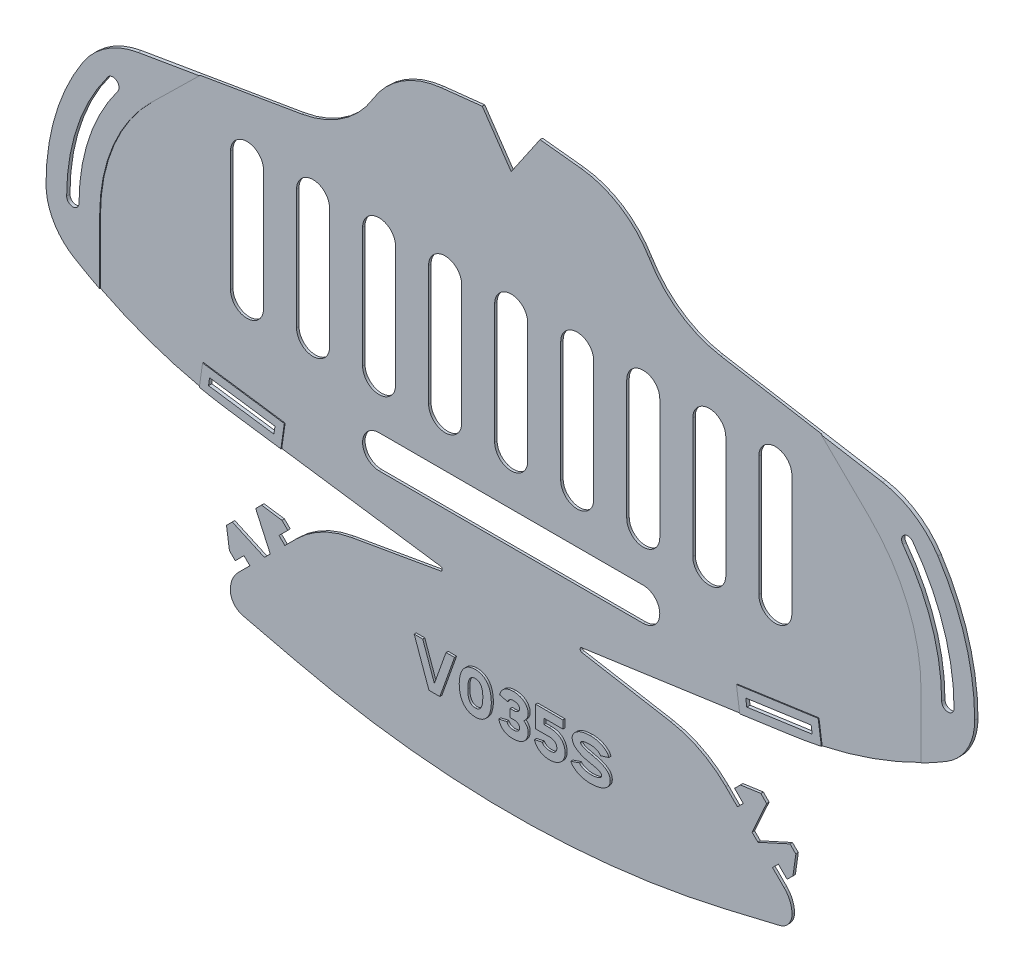
SolidWorks part; units mm, degrees
ref_plane "Front Plane" through (0, 0, 0) normal (0, 0, 1) x (1, 0, 0)
ref_plane "Top Plane" through (0, 0, 0) normal (0, 1, 0) x (1, 0, 0)
ref_plane "Right Plane" through (0, 0, 0) normal (1, 0, 0) x (0, 0, -1)
sketch "Sketch1" plane through (0, 0, 0) normal (0, 0, 1) x (1, 0, 0)
  line L0 (0, 0) -> (0, -145) construction
  line L1 (-14, -102) -> (14, -102) construction
  line L2 (-112.5, -69) -> (112.5, -69) construction
  line L3 (0, -10.2352) -> (-7, 0)
  line L4 (0, -10.2352) -> (7, 0)
  line L5 (7, 0) -> (16.9419, -1.0768)
  line L6 (-90.1804, -30.1909) -> (-50.7439, -23.5)
  line L7 (90.1804, -30.1909) -> (50.7439, -23.5)
  line L8 (-14, -102) -> (-68.2662, -94.2919)
  line L9 (-7, 0) -> (-16.9419, -1.0768)
  line L10 (14, -102) -> (68.2662, -94.2919)
  line L11 (-103.5977, -39) -> (-103.5977, -69) construction
  line L12 (-14, -102) -> (-38.6266, -106.305)
  line L13 (-52, -113.2546) -> (-54.8283, -116.0832)
  line L14 (52, -113.2546) -> (54.8283, -116.0832)
  line L15 (14, -102) -> (38.6266, -106.305)
  line L16 (-54.8283, -116.0832) -> (-56.2426, -114.669)
  line L17 (-56.2426, -114.669) -> (-54.1214, -112.5476)
  line L18 (-54.1214, -112.5476) -> (-55.5356, -111.1334)
  line L19 (-55.5356, -111.1334) -> (-60.4854, -110.4265)
  line L20 (-60.4854, -110.4265) -> (-68.9703, -118.9122)
  line L21 (-64.7275, -123.1546) -> (-63.3132, -124.5688)
  line L22 (-63.3132, -124.5688) -> (-66.1415, -127.3973)
  line L23 (-64.7275, -123.1546) -> (-66.8487, -125.2761)
  line L24 (-66.8487, -125.2761) -> (-68.263, -123.8619)
  line L25 (-68.9703, -118.9122) -> (-68.263, -123.8619)
  line L26 (68.9703, -118.9122) -> (68.263, -123.8619)
  line L27 (66.8487, -125.2761) -> (68.263, -123.8619)
  line L28 (64.7275, -123.1546) -> (66.8487, -125.2761)
  line L29 (63.3132, -124.5688) -> (66.1415, -127.3973)
  line L30 (64.7275, -123.1546) -> (63.3132, -124.5688)
  line L31 (60.4854, -110.4265) -> (68.9703, -118.9122)
  line L32 (55.5356, -111.1334) -> (60.4854, -110.4265)
  line L33 (54.1214, -112.5476) -> (55.5356, -111.1334)
  line L34 (56.2426, -114.669) -> (54.1214, -112.5476)
  line L35 (54.8283, -116.0832) -> (56.2426, -114.669)
  line L36 (-64.9691, -135.8852) -> (-52.4361, -138.8607)
  line L37 (64.9691, -135.8852) -> (52.4361, -138.8607)
  line L38 (-68.9703, -118.9122) -> (-64.7275, -123.1546) construction
  line L39 (-60.4854, -110.4265) -> (-56.2426, -114.669) construction
  arc A0 (-16.9419, -1.0768) -> (-33.4614, -11.6696) centre (-14.5729, -22.9489) ccw
  arc A1 (-33.4614, -11.6696) -> (-50.7439, -23.5) centre (-54.9257, 1.1478) cw
  arc A2 (-103.5977, -39) -> (-90.1804, -30.1909) centre (-86.8349, -49.9091) cw
  arc A3 (-112.5, -69) -> (-103.5977, -39) centre (-57.5, -69) cw
  arc A4 (112.5, -69) -> (103.5977, -39) centre (57.5, -69) ccw
  arc A5 (103.5977, -39) -> (90.1804, -30.1909) centre (86.8349, -49.9091) ccw
  arc A6 (16.9419, -1.0768) -> (33.4614, -11.6696) centre (14.5729, -22.9489) cw
  arc A7 (33.4614, -11.6696) -> (50.7439, -23.5) centre (54.9257, 1.1478) ccw
  arc A8 (-112.5, -69) -> (-105.7111, -81) centre (-98.5, -69) ccw
  arc A9 (-105.7111, -81) -> (-68.2662, -94.2919) centre (-54.2032, 4.7143) ccw
  arc A10 (112.5, -69) -> (105.7111, -81) centre (98.5, -69) cw
  arc A11 (105.7111, -81) -> (68.2662, -94.2919) centre (54.2032, 4.7143) cw
  arc A12 (-38.6266, -106.305) -> (-52, -113.2546) centre (-34.3216, -130.9315) ccw
  arc A13 (38.6266, -106.305) -> (52, -113.2546) centre (34.3216, -130.9315) cw
  arc A14 (-66.1415, -127.3973) -> (-68.0451, -131.9933) centre (-61.5451, -131.9933) ccw
  arc A15 (-68.0451, -131.9933) -> (-64.9691, -135.8852) centre (-64.0451, -131.9933) ccw
  arc A16 (68.0451, -131.9933) -> (64.9691, -135.8852) centre (64.0451, -131.9933) cw
  arc A17 (66.1415, -127.3973) -> (68.0451, -131.9933) centre (61.5451, -131.9933) cw
  arc A19 (-52.4361, -138.8607) -> (0, -145) centre (0, 82) ccw
  arc A20 (52.4361, -138.8607) -> (0, -145) centre (0, 82) cw
  point P8 (0, -102)
  point P11 (0, -69)
  point P76 (0, 0)
  point P78 (0, 0)
  point P79 (0, 0)
  point P80 (0, 0)
  point P81 (0, 0)
  dimension "D5" = 55
  dimension "D11" = 20
  dimension "D13" = 25
  dimension "D16" = 14
  dimension "D15" = 22
  dimension "D18" = 100
  dimension "D22" = 25
  dimension "D31" = 6.5
  dimension "D32" = 4
  dimension "D34" = 227
  dimension "D1" = 145
  dimension "D2" = 28
  dimension "D3" = 43
  dimension "D4" = 76
  dimension "D6" = 225
  dimension "D7" = 14
  dimension "D8" = 12.4
  dimension "D9" = 10
  dimension "D10" = 30
  dimension "D12" = 40
  dimension "D14" = 45.5
  dimension "D17" = 12
  dimension "D19" = 18
  dimension "D20" = 25
  dimension "D21" = 4
  dimension "D23" = 38
  dimension "D24" = 2
  dimension "D25" = 3
  dimension "D26" = 2
  dimension "D27" = 18
  dimension "D29" = 8
  dimension "D30" = 4
extrude "Main Shape" add sketch "Sketch1" along normal blind 0.6
sketch "Sketch2" plane through (0, 0, 0.6) normal (0, 0, 1) x (1, 0, 0)
  line L0 (0, -55) -> (0, 55) construction
  arc A0 (-96.3, -39.9) -> (-106, -69) centre (-57.5, -69) ccw construction
  arc A1 (-97.5, -39) -> (-107.5, -69) centre (-57.5, -69) ccw
  arc A2 (-95.1, -40.8) -> (-104.5, -69) centre (-57.5, -69) ccw
  arc A3 (-95.1, -40.8) -> (-97.5, -39) centre (-96.3, -39.9) ccw
  arc A4 (-107.5, -69) -> (-104.5, -69) centre (-106, -69) ccw
  arc A6 (-103.5977, -39) -> (-112.5, -69) centre (-57.5, -69) ccw construction
  arc A7 (96.3, -39.9) -> (106, -69) centre (57.5, -69) cw construction
  arc A8 (97.5, -39) -> (107.5, -69) centre (57.5, -69) cw
  arc A9 (95.1, -40.8) -> (104.5, -69) centre (57.5, -69) cw
  arc A10 (95.1, -40.8) -> (97.5, -39) centre (96.3, -39.9) cw
  arc A11 (107.5, -69) -> (104.5, -69) centre (106, -69) cw
  point P3 (-103.5111, -53.663)
  point P19 (103.5111, -53.663)
  dimension "D1" = 5
  dimension "D2" = 1.5
extrude "Elastic Attachment Points" cut sketch "Sketch2" against normal through all
sketch "Sketch7" plane through (0, 0, 0.6) normal (0, 0, 1) x (1, 0, 0)
  line L0 (-99.5, -69) -> (-99.5, -84.4384)
  line L1 (-86.8939, -39) -> (-75.3319, -27.6717)
  line L2 (-50.7439, -23.5) -> (-90.1804, -30.1909) construction
  line L3 (-75.3319, -27.6717) -> (-90.1804, -30.1909)
  line L4 (0, -55) -> (0, 55) construction
  line L5 (75.3319, -27.6717) -> (90.1804, -30.1909)
  line L6 (86.8939, -39) -> (75.3319, -27.6717)
  line L7 (99.5, -69) -> (99.5, -84.4384)
  arc A0 (-99.5, -69) -> (-86.8939, -39) centre (-57.5, -69) cw
  arc A1 (-95.1, -40.8) -> (-104.5, -69) centre (-57.5, -69) ccw construction
  arc A2 (-105.7111, -81) -> (-68.2662, -94.2919) centre (-54.2032, 4.7143) ccw construction
  arc A3 (-112.5, -69) -> (-105.7111, -81) centre (-98.5, -69) ccw construction
  arc A4 (-103.5977, -39) -> (-112.5, -69) centre (-57.5, -69) ccw construction
  arc A5 (-90.1804, -30.1909) -> (-103.5977, -39) centre (-86.8349, -49.9091) ccw construction
  arc A6 (-105.7111, -81) -> (-99.5, -84.4384) centre (-54.2032, 4.7143) ccw
  arc A7 (-112.5, -69) -> (-105.7111, -81) centre (-98.5, -69) ccw
  arc A8 (-103.5977, -39) -> (-112.5, -69) centre (-57.5, -69) ccw
  arc A9 (-90.1804, -30.1909) -> (-103.5977, -39) centre (-86.8349, -49.9091) ccw
  arc A10 (90.1804, -30.1909) -> (103.5977, -39) centre (86.8349, -49.9091) cw
  arc A11 (103.5977, -39) -> (112.5, -69) centre (57.5, -69) cw
  arc A12 (112.5, -69) -> (105.7111, -81) centre (98.5, -69) cw
  arc A13 (105.7111, -81) -> (99.5, -84.4384) centre (54.2032, 4.7143) cw
  arc A14 (99.5, -69) -> (86.8939, -39) centre (57.5, -69) ccw
  arc A15 (-107.5, -69) -> (-104.5, -69) centre (-106, -69) ccw construction
  arc A16 (-95.1, -40.8) -> (-97.5, -39) centre (-96.3, -39.9) ccw construction
  arc A17 (-97.5, -39) -> (-107.5, -69) centre (-57.5, -69) ccw construction
  arc A18 (-107.5, -69) -> (-104.5, -69) centre (-106, -69) ccw
  arc A19 (-95.1, -40.8) -> (-97.5, -39) centre (-96.3, -39.9) ccw
  arc A20 (-95.1, -40.8) -> (-104.5, -69) centre (-57.5, -69) ccw
  arc A21 (-97.5, -39) -> (-107.5, -69) centre (-57.5, -69) ccw
  arc A22 (104.5, -69) -> (107.5, -69) centre (106, -69) ccw construction
  arc A23 (97.5, -39) -> (95.1, -40.8) centre (96.3, -39.9) ccw construction
  arc A24 (104.5, -69) -> (95.1, -40.8) centre (57.5, -69) ccw construction
  arc A25 (107.5, -69) -> (97.5, -39) centre (57.5, -69) ccw construction
  arc A26 (104.5, -69) -> (107.5, -69) centre (106, -69) ccw
  arc A27 (97.5, -39) -> (95.1, -40.8) centre (96.3, -39.9) ccw
  arc A28 (104.5, -69) -> (95.1, -40.8) centre (57.5, -69) ccw
  arc A29 (107.5, -69) -> (97.5, -39) centre (57.5, -69) ccw
  dimension "D1" = 5
extrude "Reinforced Attachment Points" add sketch "Sketch7" along normal blind 0.2
sketch "Sketch6" plane through (0, 0, 0.6) normal (0, 0, 1) x (1, 0, 0)
  line L0 (-73.1225, -91.5821) -> (-57.2815, -93.8322)
  line L1 (-57.2815, -93.8322) -> (-57.0283, -92.05)
  line L2 (-57.0283, -92.05) -> (-72.8693, -89.8)
  line L3 (-72.8693, -89.8) -> (-73.1225, -91.5821)
  line L4 (-68.2662, -94.2919) -> (-14, -102) construction
  line L5 (-64.9488, -90.925) -> (-65.202, -92.7071) construction
  line L13 (0, -0.44) -> (0, 0.44) construction
  line L14 (64.9488, -90.925) -> (65.202, -92.7071) construction
  line L15 (73.1225, -91.5821) -> (72.8693, -89.8)
  line L16 (57.0283, -92.05) -> (57.2815, -93.8322)
  line L22 (57.0283, -92.05) -> (72.8693, -89.8)
  line L24 (73.1225, -91.5821) -> (57.2815, -93.8322)
  dimension "D1" = 2
  dimension "D2" = 16
  dimension "D3" = 52
  dimension "D4" = 1.8
extrude "Tab Slits" cut sketch "Sketch6" against normal through all
sketch "Sketch9" plane through (0, 0, 0.6) normal (0, 0, 1) x (1, 0, 0)
  line L4 (-57.2815, -93.8322) -> (-57.0283, -92.05) construction
  line L5 (-73.1225, -91.5821) -> (-57.2815, -93.8322) construction
  line L6 (-72.8693, -89.8) -> (-73.1225, -91.5821) construction
  line L7 (-57.0283, -92.05) -> (-72.8693, -89.8) construction
  line L12 (-57.2815, -93.8322) -> (-57.0283, -92.05)
  line L13 (-73.1225, -91.5821) -> (-57.2815, -93.8322)
  line L14 (-72.8693, -89.8) -> (-73.1225, -91.5821)
  line L15 (-57.0283, -92.05) -> (-72.8693, -89.8)
  line L16 (-55.5826, -96.0935) -> (-54.767, -90.3512)
  line L17 (-68.2662, -94.2919) -> (-14, -102) construction
  line L18 (-54.767, -90.3512) -> (-74.5682, -87.5386)
  line L19 (-74.5682, -87.5386) -> (-75.3475, -93.0248)
  line L20 (-68.2662, -94.2919) -> (-55.5826, -96.0935)
  line L21 (0, -0.44) -> (0, 0.44) construction
  line L22 (68.2662, -94.2919) -> (55.5826, -96.0935)
  line L23 (74.5682, -87.5386) -> (75.3475, -93.0248)
  line L24 (54.767, -90.3512) -> (74.5682, -87.5386)
  line L25 (55.5826, -96.0935) -> (54.767, -90.3512)
  line L26 (57.0283, -92.05) -> (72.8693, -89.8)
  line L27 (72.8693, -89.8) -> (73.1225, -91.5821)
  line L28 (73.1225, -91.5821) -> (57.2815, -93.8322)
  line L29 (57.2815, -93.8322) -> (57.0283, -92.05)
  arc A0 (-99.5, -84.4384) -> (-68.2662, -94.2919) centre (-54.2032, 4.7143) ccw construction
  arc A1 (-75.3475, -93.0248) -> (-68.2662, -94.2919) centre (-54.2032, 4.7143) ccw
  arc A2 (75.3475, -93.0248) -> (68.2662, -94.2919) centre (54.2032, 4.7143) cw
  dimension "D1" = 2
  dimension "D2" = 2
  dimension "D3" = 2
extrude "Reinforced Tab Slits" add sketch "Sketch9" along normal blind 0.2
sketch "Sketch11" plane through (0, 0, 0.6) normal (0, 0, 1) x (1, 0, 0)
  line L0 (-67.5562, -117.4979) -> (-59.7778, -121.0331)
  line L1 (-60.4854, -110.4265) -> (-68.9703, -118.9122) construction
  line L2 (-59.7778, -121.0331) -> (-58.3637, -119.6188)
  line L3 (-58.3637, -119.6188) -> (-61.8996, -111.8408)
  line L4 (-61.8996, -111.8408) -> (-67.5562, -117.4979)
  line L6 (-58.3637, -119.6188) -> (-54.8283, -116.0832) construction
  line L7 (-59.7778, -121.0331) -> (-63.3132, -124.5688) construction
  line L10 (0, -0.44) -> (0, 0.44) construction
  line L11 (59.7778, -121.0331) -> (63.3132, -124.5688) construction
  line L12 (58.3637, -119.6188) -> (54.8283, -116.0832) construction
  line L13 (61.8996, -111.8408) -> (67.5562, -117.4979)
  line L14 (58.3637, -119.6188) -> (61.8996, -111.8408)
  line L15 (59.7778, -121.0331) -> (58.3637, -119.6188)
  line L16 (67.5562, -117.4979) -> (59.7778, -121.0331)
  dimension "D1" = 2
  dimension "D2" = 2
  dimension "D3" = 5
extrude "Tab Flex Relief" cut sketch "Sketch11" against normal through all both and the other way through all
sketch "Sketch3" plane through (0, 0, 0.6) normal (0, 0, 1) x (1, 0, 0)
  line L3 (0, -10.2352) -> (0, -145) construction
  line L4 (-106, -69) -> (-96.3, -69) construction
  line L5 (-96.3, -69) -> (-96.3, -39.9) construction
  line L427 (0, -39.9) -> (0, -69) construction
  line L428 (4, -39.9) -> (4, -69)
  line L429 (-4, -39.9) -> (-4, -69)
  line L444 (-16, -39.9) -> (-16, -69) construction
  line L447 (-12, -39.9) -> (-12, -69)
  line L450 (-20, -39.9) -> (-20, -69)
  line L451 (-32, -39.9) -> (-32, -69) construction
  line L455 (-28, -39.9) -> (-28, -69)
  line L456 (-36, -39.9) -> (-36, -69)
  line L836 (-32, -85) -> (32, -85) construction
  line L837 (-32, -81) -> (32, -81)
  line L838 (-32, -89) -> (32, -89)
  line L839 (-64, -73) -> (64, -73) construction
  line L933 (-48, -39.9) -> (-48, -69) construction
  line L934 (-44, -39.9) -> (-44, -69)
  line L935 (-52, -39.9) -> (-52, -69)
  line L936 (-64, -39.9) -> (-64, -69) construction
  line L937 (-60, -39.9) -> (-60, -69)
  line L938 (-68, -39.9) -> (-68, -69)
  line L939 (16, -39.9) -> (16, -69) construction
  line L940 (12, -39.9) -> (12, -69)
  line L941 (20, -39.9) -> (20, -69)
  line L942 (32, -39.9) -> (32, -69) construction
  line L943 (28, -39.9) -> (28, -69)
  line L944 (36, -39.9) -> (36, -69)
  line L945 (48, -39.9) -> (48, -69) construction
  line L946 (44, -39.9) -> (44, -69)
  line L947 (52, -39.9) -> (52, -69)
  line L948 (64, -39.9) -> (64, -69) construction
  line L949 (60, -39.9) -> (60, -69)
  line L950 (68, -39.9) -> (68, -69)
  arc A2 (-52.4361, -138.8607) -> (52.4361, -138.8607) centre (0, 82) ccw construction
  arc A21 (4, -39.9) -> (-4, -39.9) centre (0, -39.9) ccw
  arc A22 (-4, -69) -> (4, -69) centre (0, -69) ccw
  arc A23 (-12, -39.9) -> (-20, -39.9) centre (-16, -39.9) ccw
  arc A24 (-20, -69) -> (-12, -69) centre (-16, -69) ccw
  arc A25 (-28, -39.9) -> (-36, -39.9) centre (-32, -39.9) ccw
  arc A26 (-36, -69) -> (-28, -69) centre (-32, -69) ccw
  arc A27 (-44, -39.9) -> (-52, -39.9) centre (-48, -39.9) ccw
  arc A28 (-52, -69) -> (-44, -69) centre (-48, -69) ccw
  arc A29 (-60, -39.9) -> (-68, -39.9) centre (-64, -39.9) ccw
  arc A30 (-68, -69) -> (-60, -69) centre (-64, -69) ccw
  arc A31 (12, -39.9) -> (20, -39.9) centre (16, -39.9) cw
  arc A32 (20, -69) -> (12, -69) centre (16, -69) cw
  arc A33 (28, -39.9) -> (36, -39.9) centre (32, -39.9) cw
  arc A34 (36, -69) -> (28, -69) centre (32, -69) cw
  arc A35 (44, -39.9) -> (52, -39.9) centre (48, -39.9) cw
  arc A36 (52, -69) -> (44, -69) centre (48, -69) cw
  arc A37 (60, -39.9) -> (68, -39.9) centre (64, -39.9) cw
  arc A38 (68, -69) -> (60, -69) centre (64, -69) cw
  arc A39 (-32, -81) -> (-32, -89) centre (-32, -85) ccw
  arc A40 (32, -89) -> (32, -81) centre (32, -85) ccw
  point P3 (-16, -54.45)
  point P18 (-32, -54.45)
  point P30 (-48, -54.45)
  point P37 (-64, -54.45)
  point P43 (16, -54.45)
  point P50 (32, -54.45)
  point P57 (48, -54.45)
  point P64 (64, -54.45)
  point P71 (0, -85)
  point P414 (0, -54.45)
  dimension "D5" = 8
  dimension "D1" = 8
  dimension "D2" = 5
  dimension "D3" = 8
  dimension "D4" = 8
extrude "Breathing Slits" cut sketch "Sketch3" against normal through all
sketch "Sketch8" plane through (0, 0, 0.6) normal (0, 0, 1) x (1, 0, 0)
  line L0 (-67.0266, -128.5) -> (67.0266, -128.5) construction
  line L1 (0, -10.2352) -> (0, -145) construction
  arc A0 (-52.4361, -138.8607) -> (52.4361, -138.8607) centre (0, 82) ccw construction
  arc A1 (-66.1415, -127.3973) -> (-68.0451, -131.9933) centre (-61.5451, -131.9933) ccw construction
  text T0 "<b>V035S</b>\r\n" font "Double Porter 3" height 10
  point P9 (0, -128.5)
  dimension "D2" = 16.5
extrude "Version Number" add sketch "Sketch8" along normal blind 0.5
fillet "Fillet1" radius 0.5 2 edges at (-14, -102, 0.3) (14, -102, 0.3)
